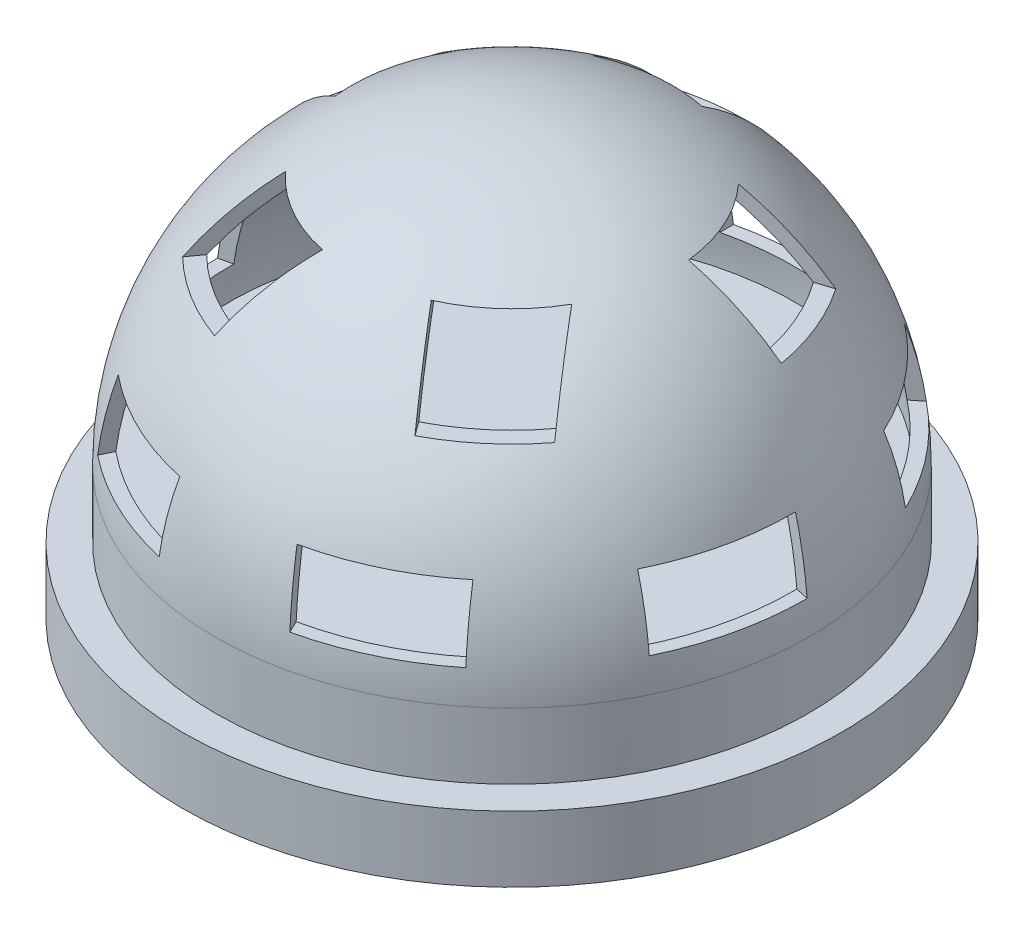
SolidWorks part; units mm, degrees
ref_plane "Piano frontale" through (0, 0, 0) normal (0, 0, 1) x (1, 0, 0)
ref_plane "Piano superiore" through (0, 0, 0) normal (0, 1, 0) x (1, 0, 0)
ref_plane "Piano destro" through (0, 0, 0) normal (1, 0, 0) x (0, 0, -1)
sketch "Schizzo1" plane through (0, 0, 0) normal (0, 1, 0) x (1, 0, 0)
  circle A0 centre (0, 0) radius 50
  dimension "D1" = 100
extrude "Estrusione-Estrusione1" add sketch "Schizzo1" along normal blind 10
sketch "Schizzo2" plane through (0, 10, 0) normal (0, 1, 0) x (1, 0, 0)
  circle A0 centre (0, 0) radius 45
  dimension "D1" = 90
extrude "Estrusione-Estrusione2" add sketch "Schizzo2" along normal blind 10
sketch "Schizzo6" plane through (0, 0, 0) normal (1, 0, 0) x (0, 0, -1)
  line L0 (0, 119.6863) -> (0, 20) construction
  line L1 (45, 20) -> (-45, 20) construction
  line L3 (0, 65) -> (0, 63)
  line L4 (-43, 20) -> (-45, 20)
  arc A1 (-45, 20) -> (0, 65) centre (0, 20) cw
  arc A2 (-43, 20) -> (0, 63) centre (0, 20) cw
revolve "Rivoluzione9" add sketch "Schizzo6" angle 360 about L0
sketch "Schizzo14" plane through (0, 0, 0) normal (0, 0, 1) x (1, 0, 0)
  line L0 (-55.849, 34.931) -> (58.6414, 34.931) construction
  line L1 (-10, 34.931) -> (10, 34.931)
  line L2 (-10, 34.931) -> (-10, 24.931)
  line L3 (-10, 24.931) -> (10, 24.931)
  line L4 (10, 34.931) -> (10, 24.931)
  line L5 (0, -10.636) -> (0, 69.4632) construction
  dimension "D1" = 10
  dimension "D2" = 20
extrude "Taglio-Estrusione2" cut sketch "Schizzo14" against normal blind 53
sketch "Schizzo16" plane through (0, 0, 0) normal (0, 1, 0) x (1, 0, 0)
  line L0 (0, 86.685) -> (0, -85.9434) construction
pattern_circular "RipetizioneCircolare6" count 7 over 360 about axis through (0, 0, 0) along (0, 1, 0) of "Taglio-Estrusione2"
sketch "Schizzo17" plane through (0, 0, 0) normal (0, 0, 1) x (1, 0, 0)
  line L1 (-10, 47.8585) -> (5, 47.8585)
  line L2 (-10, 47.8585) -> (-10, 57.8585)
  line L3 (-10, 57.8585) -> (5, 57.8585)
  line L4 (5, 47.8585) -> (5, 57.8585)
  dimension "D1" = 10
  dimension "D2" = 15
extrude "Taglio-Estrusione3" cut sketch "Schizzo17" against normal blind 53
pattern_circular "RipetizioneCircolare7" count 5 over 360 about axis through (0, 0, 0) along (0, 1, 0) of "Taglio-Estrusione3"
